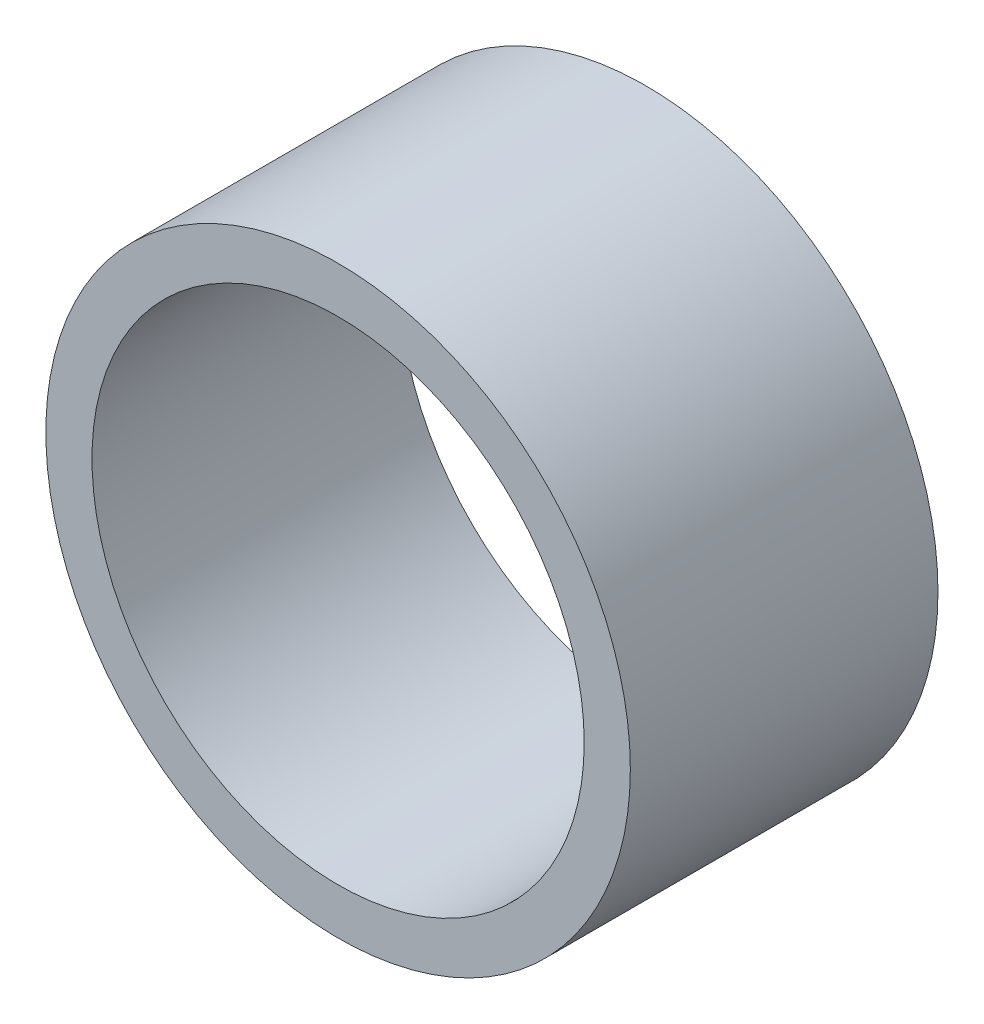
SolidWorks part; units mm, degrees
ref_plane "Alzado" through (0, 0, 0) normal (1, 0, 0) x (0, 1, 0)
ref_plane "Planta" through (0, 0, 0) normal (0, 0, 1) x (0, 1, 0)
ref_plane "Vista lateral" through (0, 0, 0) normal (0, 1, 0) x (-1, 0, 0)
sketch "Croquis1" plane through (0, 0, 0) normal (0, 0, 1) x (0, 1, 0)
  circle A0 centre (0, 0) radius 9.5
  circle A1 centre (0, 0) radius 8
  dimension "D1" = 19
  dimension "D2" = 16
extrude "Saliente-Extruir1" add sketch "Croquis1" along normal blind 10
